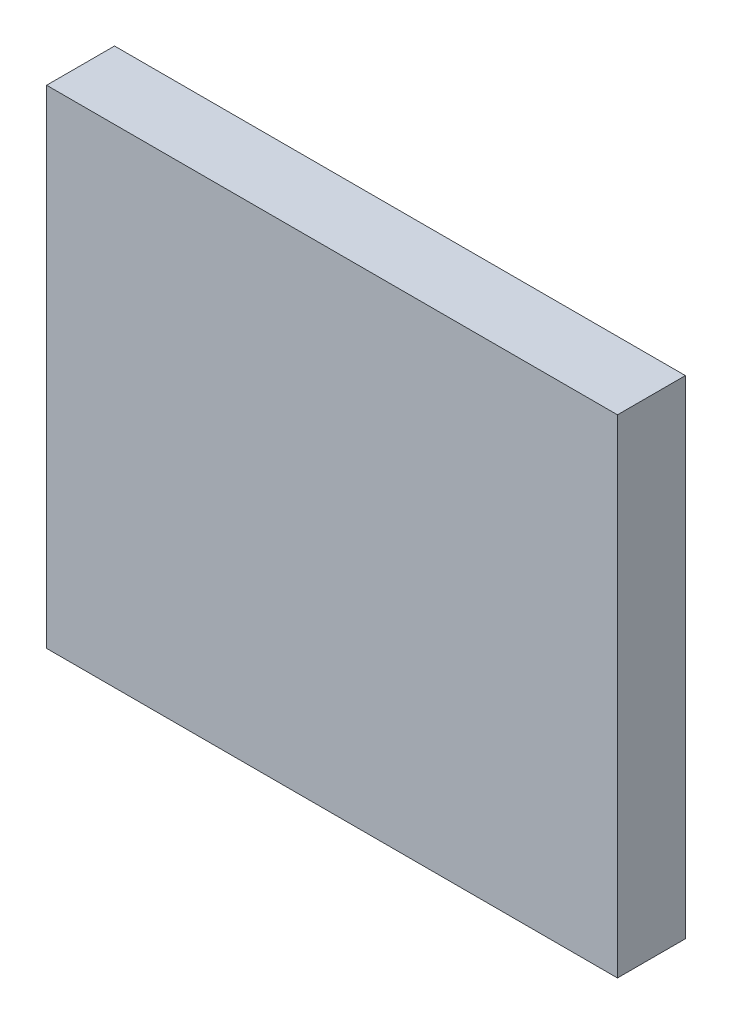
SolidWorks part; units mm, degrees
ref_plane "Front" through (0, 0, 0) normal (0, 0, 1) x (1, 0, 0)
ref_plane "Top" through (0, 0, 0) normal (0, 1, 0) x (1, 0, 0)
ref_plane "Right" through (0, 0, 0) normal (1, 0, 0) x (0, 0, -1)
sketch "Sketch1" plane through (0, 0, 0) normal (0, 0, 1) x (1, 0, 0)
  line L0 (-54.3546, 28.2718) -> (-54.3546, -43.5316)
  line L1 (-54.3546, 28.2718) -> (29.6843, 28.2718)
  line L2 (29.6843, 28.2718) -> (29.6843, -43.5316)
  line L3 (-54.3546, -43.5316) -> (29.6843, -43.5316)
  line L5 (-33.7474, 42.7612) -> (-24.7317, 42.7612)
  line L6 (-33.7474, 42.7612) -> (-33.7474, 28.2718)
  line L7 (-33.7474, 28.2718) -> (-24.7317, 28.2718)
  line L8 (-24.7317, 42.7612) -> (-24.7317, 28.2718)
  line L9 (-1.5486, 42.7612) -> (7.4671, 42.7612)
  line L10 (-1.5486, 42.7612) -> (-1.5486, 28.2718)
  line L11 (-1.5486, 28.2718) -> (7.4671, 28.2718)
  line L12 (7.4671, 42.7612) -> (7.4671, 28.2718)
  circle A0 centre (-26.9856, 7.9865) radius 13.0276
  circle A1 centre (3.9252, 7.9865) radius 12.7826
extrude "Boss-Extrude3" add sketch "Sketch1" along normal blind 10 contours L2 L3 L0 L1
